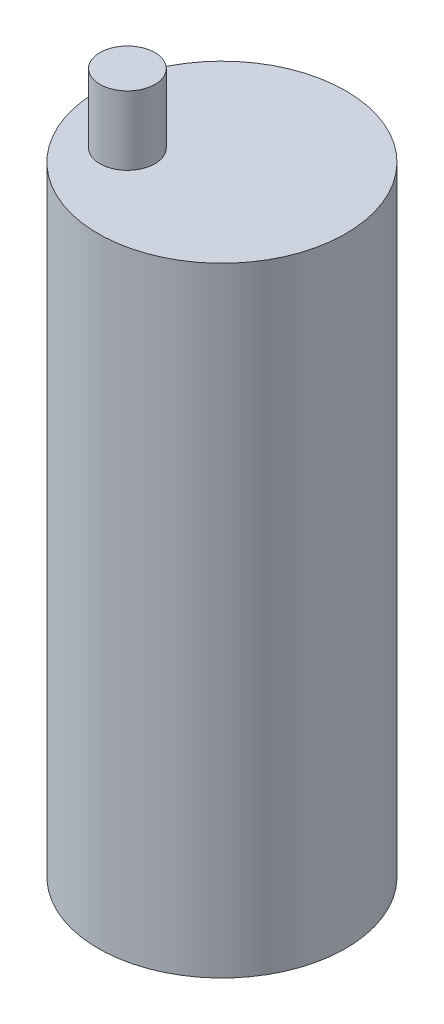
SolidWorks part; units mm, degrees
ref_plane "前视基准面" through (0, 0, 0) normal (0, 0, 1) x (1, 0, 0)
ref_plane "上视基准面" through (0, 0, 0) normal (0, 1, 0) x (1, 0, 0)
ref_plane "右视基准面" through (0, 0, 0) normal (1, 0, 0) x (0, 0, -1)
sketch "草图1" plane through (0, 0, 0) normal (0, 1, 0) x (1, 0, 0)
  circle A0 centre (0, 0) radius 9
extrude "凸台-拉伸1" add sketch "草图1" along normal blind 45
sketch "草图2" plane through (0, 45, 0) normal (0, 1, 0) x (1, 0, 0)
  circle A0 centre (-4.3396, -2.5332) radius 2
extrude "凸台-拉伸2" add sketch "草图2" along normal blind 5
